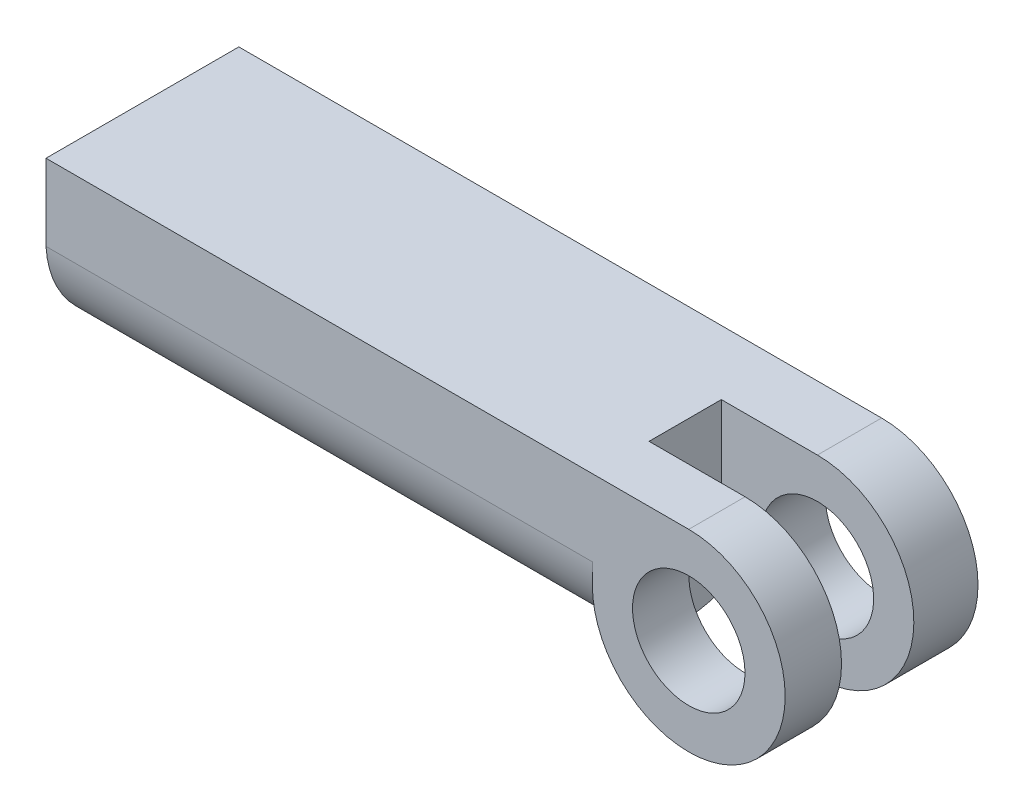
SolidWorks part; units mm, degrees
ref_plane "Front Plane" through (0, 0, 0) normal (0, 0, 1) x (1, 0, 0)
ref_plane "Top Plane" through (0, 0, 0) normal (0, 1, 0) x (1, 0, 0)
ref_plane "Right Plane" through (0, 0, 0) normal (1, 0, 0) x (0, 0, -1)
sketch "Sketch1" plane through (0, 0, 0) normal (0, 0, 1) x (1, 0, 0)
  line L0 (-50.0444, 27.5035) -> (29.9556, 27.5035)
  line L1 (17.9556, 15.5035) -> (17.9556, 6.1362)
  line L2 (17.9556, 6.1362) -> (-39.5444, 6.0035)
  line L3 (-39.5444, 6.0035) -> (-39.5444, 5.0152)
  line L4 (-39.5444, 5.0152) -> (-48.5721, 5.0152)
  line L5 (-48.5721, 5.0152) -> (-48.5721, 6.0035)
  line L6 (-48.5721, 6.0035) -> (-50.0444, 6.0035)
  line L7 (-50.0444, 6.0035) -> (-50.0444, 27.5035)
  arc A0 (29.9556, 27.5035) -> (17.9556, 15.5035) centre (29.9556, 15.5035) cw
  circle A1 centre (29.9556, 15.5035) radius 7
extrude "Boss-Extrude1" add sketch "Sketch1" along normal blind 24
ref_plane "Plane1" through (50, 0, 0) normal (1, 0, 0) x (0, 0, -1)
sketch "Sketch2" plane through (50, 0, 0) normal (1, 0, 0) x (0, 0, -1)
  line L0 (-16.9863, 27.5035) -> (-7.9863, 27.5035)
  line L1 (-24, 27.5035) -> (0, 27.5035) construction
  line L2 (-16.9863, 27.5035) -> (-16.9863, 3.5035)
  line L3 (-24, 3.5035) -> (0, 3.5035) construction
  line L4 (-16.9863, 3.5035) -> (-7.9863, 3.5035)
  line L5 (-7.9863, 3.5035) -> (-7.9863, 27.5035)
  point P5 (-12.4863, 27.5035)
extrude "Cut-Extrude1" cut sketch "Sketch2" against normal blind 32
sketch "Sketch3" plane through (-50.0444, 0, 0) normal (-1, 0, 0) x (0, 0, 1)
  line L3 (0, 27.5035) -> (24, 27.5035)
  line L8 (24, 27.5035) -> (24, 19.5035)
  line L9 (24, 27.5035) -> (24, 6.0035) construction
  line L10 (0, 27.5035) -> (0, 19.5035)
  line L11 (0, 27.5035) -> (0, 6.0035) construction
  line L12 (24, 6.0035) -> (0, 6.0035) construction
  arc A3 (0, 19.5035) -> (12, 6.0035) centre (12.75, 18.7535) ccw
  arc A4 (24, 19.5035) -> (12, 6.0035) centre (11.25, 18.7535) cw
extrude "Cut-Extrude3" cut sketch "Sketch3" against normal blind 68 flip side to cut
sketch "Sketch4" plane through (-50.0444, 0, 0) normal (-1, 0, 0) x (0, 0, 1)
  line L2 (0.1371, 16.7436) -> (23.8629, 16.7436) construction
  arc A0 (0, 18.0035) -> (0.3984, 15.5035) centre (12.75, 18.7535) ccw construction
  arc A1 (23.6016, 15.5035) -> (24, 18.0035) centre (11.25, 18.7535) ccw construction
  circle A2 centre (12, 17.2181) radius 9
extrude "Cut-Extrude4" cut sketch "Sketch4" against normal blind 67
